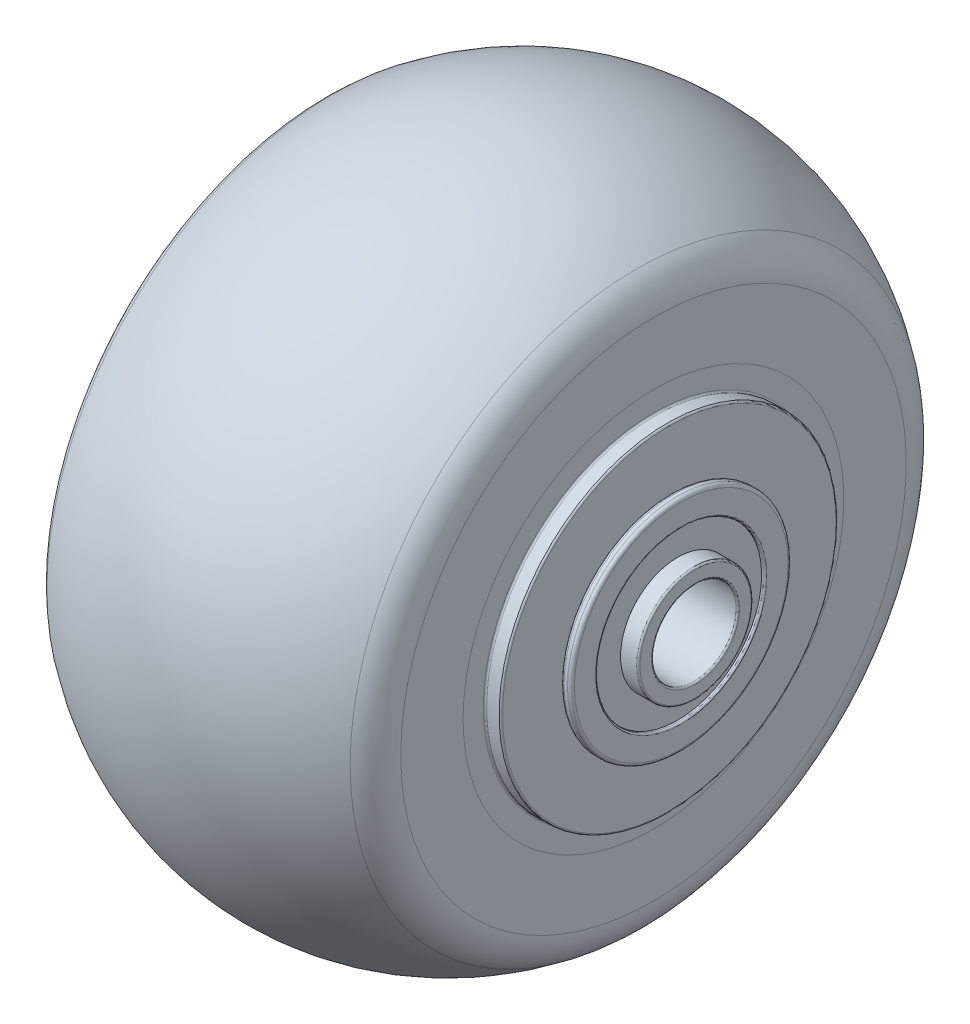
SolidWorks part; units mm, degrees
ref_plane "Front Plane" through (0, 0, 0) normal (0, 0, 1) x (1, 0, 0)
ref_plane "Top Plane" through (0, 0, 0) normal (0, 1, 0) x (1, 0, 0)
ref_plane "Right Plane" through (0, 0, 0) normal (1, 0, 0) x (0, 0, -1)
sketch "Sketch1" plane through (0, 0, 0) normal (0, 0, 1) x (1, 0, 0)
  line L0 (-27.7812, 0) -> (27.7812, 0) construction
  line L1 (0, 50.8) -> (0, -50.8) construction
  line L2 (29.591, -16.637) -> (29.591, -15.0812) construction
  line L3 (-25.4, 28.702) -> (25.4, 28.702) construction
  line L35 (0, -6.35) -> (31.75, -6.35)
  line L36 (31.75, -8.6416) -> (31.75, -6.35)
  line L37 (29.591, -8.6416) -> (31.75, -8.6416)
  line L38 (29.591, -16.1184) -> (29.591, -8.6416)
  line L39 (28.5538, -16.637) -> (29.0724, -16.637)
  line L40 (27.7813, -25.4013) -> (27.7813, -15.0812)
  line L41 (28.0353, -16.1184) -> (28.0353, -15.0812)
  line L42 (28.0353, -15.0812) -> (0, -15.0813)
  line L43 (0, -50.8) -> (0, -6.35) construction
  line L57 (0, -50.8) -> (-2.159, -50.8) construction
  line L58 (28.0353, -16.1184) -> (28.5538, -16.1184) construction
  line L59 (28.5538, -16.1184) -> (29.0724, -16.1184) construction
  line L60 (29.0724, -16.1184) -> (29.591, -16.1184) construction
  line L61 (29.591, -15.0812) -> (28.0353, -15.0812) construction
  line L62 (29.591, -12.6393) -> (29.0724, -12.6393) construction
  line L63 (29.0724, -12.6393) -> (29.0724, -8.6416) construction
  line L64 (29.0724, -8.6416) -> (29.591, -8.6416) construction
  line L65 (29.0724, -16.637) -> (29.0724, -12.6393) construction
  line L66 (27.7813, -25.4013) -> (25.4, -25.4013)
  line L67 (25.4, -28.702) -> (0, -28.702)
  line L68 (25.4, 28.702) -> (25.4, -28.702) construction
  line L72 (25.4, -38.1) -> (25.4, -25.4013)
  line L78 (0, -6.3754) -> (0, -50.8) construction
  line L79 (0, 0) -> (31.75, 0) construction
  line L81 (25.4, -28.702) -> (0, -28.702)
  arc A7 (29.0724, -16.637) -> (29.591, -16.1184) centre (29.0724, -16.1184) ccw
  arc A8 (28.0353, -16.1184) -> (28.5538, -16.637) centre (28.5538, -16.1184) ccw
  arc A10 (22.86, -43.18) -> (25.4, -38.1) centre (19.05, -38.1) ccw
  arc A11 (0, -50.8) -> (22.86, -43.18) centre (0, -12.7) ccw
  point P9 (0, 28.702)
  point P14 (25.4, 0)
  dimension "D4" = 6.35
  dimension "D5" = 38.1
  dimension "Wheel Dia" = 101.6
  dimension "Hub Length" = 55.5625
  dimension "Wheel Width" = 50.8
  dimension "Hub OD" = 57.404
  dimension "Axle Dia" = 12.7
  dimension "D1" = 17.2831
  dimension "Bearing Width" = 63.5
  dimension "D10" = 0.254
  dimension "Bear OD" = 30.1625
  dimension "D2" = 1.5557
  dimension "D7" = 50.8025
sketch "Sketch2" plane through (0, 0, 0) normal (0, 0, 1) x (1, 0, 0)
  line L0 (28.0353, -15.0812) -> (0, -15.0813) construction
  line L1 (28.0352, -16.1184) -> (28.0353, -15.0812) construction
  line L2 (28.5538, -16.637) -> (29.0724, -16.637) construction
  line L3 (29.591, -16.1184) -> (29.591, -8.6416) construction
  line L4 (29.591, -8.6416) -> (31.75, -8.6416) construction
  line L5 (31.75, -8.6416) -> (31.75, -6.35) construction
  line L6 (0, -6.35) -> (31.75, -6.35) construction
  line L7 (28.0353, -15.0812) -> (-28.0353, -15.0812)
  line L8 (28.0352, -16.1184) -> (28.0353, -15.0812)
  line L9 (28.5538, -16.637) -> (29.0724, -16.637)
  line L10 (29.591, -16.1184) -> (29.591, -12.6393)
  line L11 (28.5538, -8.6416) -> (31.75, -8.6416)
  line L12 (31.75, -8.6416) -> (31.75, -6.35)
  line L13 (-31.75, -6.35) -> (31.75, -6.35)
  line L16 (0, -28.702) -> (0, -50.8) construction
  line L17 (-31.75, -8.6416) -> (-31.75, -6.35)
  line L18 (-28.5538, -8.6416) -> (-31.75, -8.6416)
  line L19 (-29.591, -16.1184) -> (-29.591, -12.6393)
  line L20 (-28.5538, -16.637) -> (-29.0724, -16.637)
  line L21 (-28.0353, -16.1184) -> (-28.0353, -15.0812)
  line L22 (29.591, -12.6393) -> (28.5538, -12.6393)
  line L23 (28.5538, -12.6393) -> (28.5538, -8.6416)
  line L25 (25.4, -28.702) -> (0, -28.702) construction
  line L26 (25.4, -38.1) -> (25.4, -25.4013) construction
  line L27 (25.4, -28.702) -> (-25.4, -28.702)
  line L28 (25.4, -38.1) -> (25.4, -28.702)
  line L37 (-28.5538, -12.6393) -> (-28.5538, -8.6416)
  line L38 (-29.591, -12.6393) -> (-28.5538, -12.6393)
  line L39 (-25.4, -38.1) -> (-25.4, -28.702)
  arc A0 (28.0352, -16.1184) -> (28.5538, -16.637) centre (28.5538, -16.1184) ccw construction
  arc A1 (29.0724, -16.637) -> (29.591, -16.1184) centre (29.0724, -16.1184) ccw construction
  arc A2 (28.0352, -16.1184) -> (28.5538, -16.637) centre (28.5538, -16.1184) ccw
  arc A3 (29.0724, -16.637) -> (29.591, -16.1184) centre (29.0724, -16.1184) ccw
  arc A6 (-29.0724, -16.637) -> (-29.591, -16.1184) centre (-29.0724, -16.1184) cw
  arc A7 (-28.0353, -16.1184) -> (-28.5538, -16.637) centre (-28.5538, -16.1184) cw
  arc A8 (22.86, -43.18) -> (25.4, -38.1) centre (19.05, -38.1) ccw construction
  arc A9 (0, -50.8) -> (22.86, -43.18) centre (0, -12.7) ccw construction
  arc A10 (22.86, -43.18) -> (25.4, -38.1) centre (19.05, -38.1) ccw
  arc A11 (-22.86, -43.18) -> (22.86, -43.18) centre (0, -12.7) ccw
  arc A12 (-22.86, -43.18) -> (-25.4, -38.1) centre (-19.05, -38.1) cw
revolve "Revolve1" add sketch "Sketch2" angle 360 about L0
sketch "Sketch3" plane through (0, 0, 0) normal (0, 0, 1) x (1, 0, 0)
  line L14 (28.0353, -15.0812) -> (0, -15.0813) construction
  line L15 (0, -15.0813) -> (0, -28.702) construction
  line L21 (27.7813, -25.4013) -> (27.7813, -15.0812) construction
  line L22 (27.7813, -25.4013) -> (25.4, -25.4013) construction
  line L23 (25.4, -38.1) -> (25.4, -25.4013) construction
  line L24 (25.4, -28.702) -> (0, -28.702) construction
  line L25 (27.7813, -15.0812) -> (-27.7812, -15.0812)
  line L26 (27.7813, -25.4013) -> (27.7813, -15.0812)
  line L27 (27.7813, -25.4013) -> (25.4, -25.4013)
  line L28 (25.4, -28.702) -> (25.4, -25.4013)
  line L29 (25.4, -28.702) -> (-25.4, -28.702)
  line L30 (-25.4, -28.702) -> (-25.4, -25.4013)
  line L31 (-27.7812, -25.4013) -> (-25.4, -25.4013)
  line L32 (-27.7812, -25.4013) -> (-27.7812, -15.0812)
revolve "Revolve2" add sketch "Sketch3" angle 360 about L0
sketch "Sketch4" plane through (28.5538, 0, 0) normal (1, 0, 0) x (0, 0, -1)
  circle A0 centre (0, 0) radius 8.6416 construction
  circle A1 centre (0, 0) radius 12.6393
  circle A2 centre (0, 0) radius 12.6393
  circle A3 centre (0, 0) radius 8.6416
  dimension "D1" = 0
extrude "Boss-Extrude1" add sketch "Sketch4" along normal up to vertex (0.5186 mm away) separate body up to point (29.0724, -8.6416, 0)
mirror "Mirror2" about plane through (0, 0, 0) normal (1, 0, 0) of bodies 107
fillet "Fillet1" radius 0.254 6 edges at (29.591, 0, 12.6393) (31.75, 0, 8.6416) (31.75, 0, 6.35) (-31.75, 0, 6.35) (-31.75, 0, 8.6416) (-29.591, 0, 12.6393)
fillet "Fillet3" radius 0.254 4 edges at (-25.4, 0, 25.4013) (-27.7812, 0, 25.4013) (25.4, 0, 25.4013) (27.7812, 0, 25.4013)
ref_plane "Contact Plane 1" through (0, -50.8, 0) normal (0, 1, 0) x (1, 0, 0)
equation "\"D1@Sketch1\"=\"Bear OD@Sketch1\"*.573"
equation "\"D1@Fillet1\"=\"D10@Sketch1\""
equation "\"D1@Fillet3\"=\"D10@Sketch1\""
